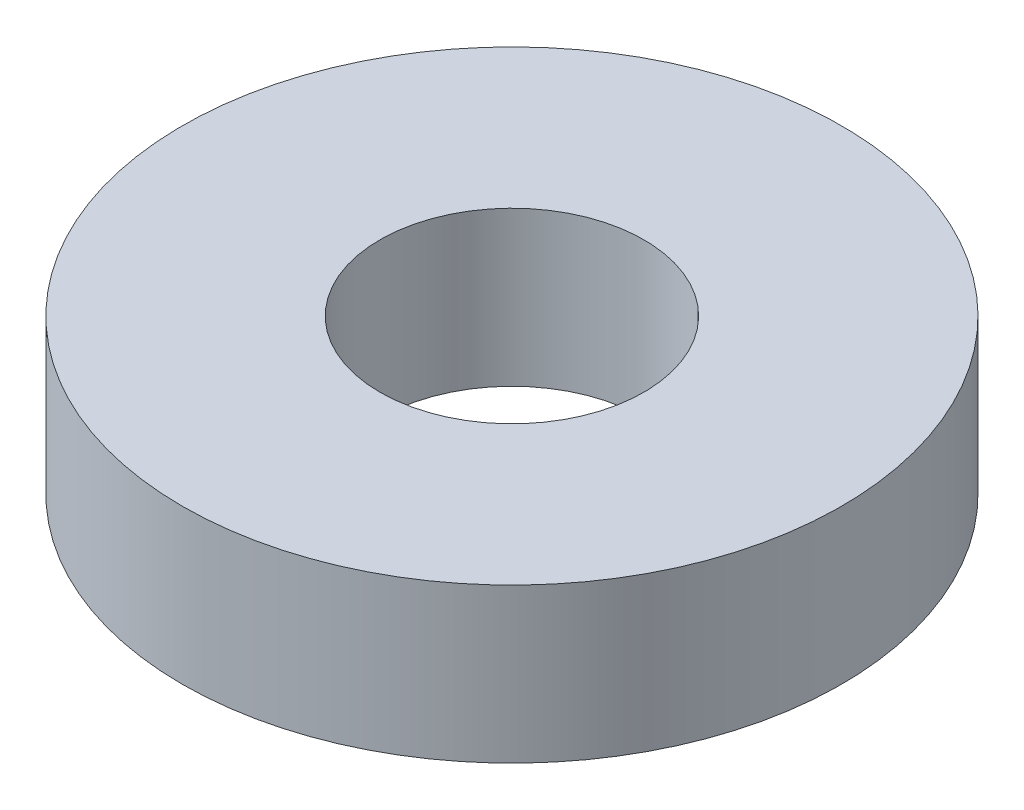
SolidWorks part; units mm, degrees
ref_plane "Front Plane" through (0, 0, 0) normal (0, 0, 1) x (1, 0, 0)
ref_plane "Top Plane" through (0, 0, 0) normal (0, 1, 0) x (1, 0, 0)
ref_plane "Right Plane" through (0, 0, 0) normal (1, 0, 0) x (0, 0, -1)
sketch "Sketch1" plane through (0, 0, 0) normal (0, 1, 0) x (1, 0, 0)
  circle A0 centre (0, 0) radius 3.9624
  dimension "OD" = 7.9248
extrude "Boss-Extrude1" add sketch "Sketch1" along normal blind 1.8542
sketch "Sketch5" plane through (0, 1.8542, 0) normal (0, 1, 0) x (-1, 0, 0)
  circle A0 centre (0, 0) radius 1.5875
  dimension "ID" = 3.175
extrude "Cut-Extrude1" cut sketch "Sketch5" against normal through all
